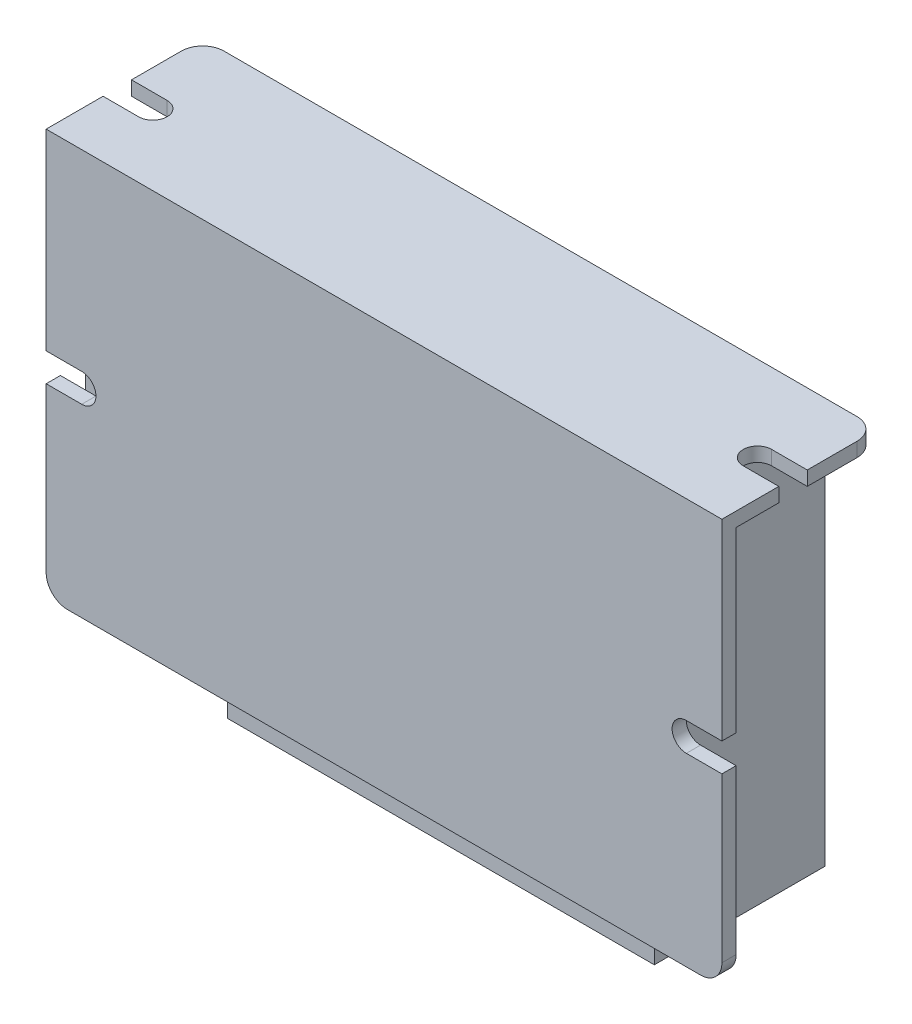
SolidWorks part; units mm, degrees
ref_plane "前视基准面" through (0, 0, 0) normal (0, 0, 1) x (1, 0, 0)
ref_plane "上视基准面" through (0, 0, 0) normal (0, 1, 0) x (1, 0, 0)
ref_plane "右视基准面" through (0, 0, 0) normal (1, 0, 0) x (0, 0, -1)
sketch "草图1" plane through (0, 0, 0) normal (0, 0, 1) x (1, 0, 0)
  line L1 (40, -27.5) -> (-40, -27.5)
  line L2 (40, -27.5) -> (40, 27.5)
  line L3 (40, 27.5) -> (-40, 27.5)
  line L4 (-40, -27.5) -> (-40, 27.5)
  line L5 (40, -27.5) -> (-40, 27.5) construction
  line L6 (40, 27.5) -> (-40, -27.5) construction
  point P0 (0, 0)
  dimension "D1" = 80
  dimension "D2" = 55
extrude "凸台-拉伸1" add sketch "草图1" along normal blind 20
sketch "草图2" plane through (0, 27.5, 0) normal (0, 1, 0) x (1, 0, 0)
  line L0 (-47.5, 0) -> (-47.5, -22)
  line L1 (-47.5, -22) -> (47.5, -22)
  line L2 (47.5, -22) -> (47.5, 0)
  line L3 (-47.5, 0) -> (-40, 0)
  line L4 (40, 0) -> (-40, 0)
  line L5 (-40, 0) -> (-40, -20)
  line L6 (-40, -20) -> (40, -20)
  line L7 (40, -20) -> (40, 0)
  line L8 (40, 0) -> (-40, 0)
  line L9 (40, -20) -> (-40, -20) construction
  line L12 (40, 0) -> (47.5, 0)
  line L13 (0, 0) -> (0, -13.9704) construction
  dimension "D2" = 95
  dimension "D3" = 2
  dimension "D1" = 0
extrude "凸台-拉伸2" add sketch "草图2" along normal blind 2 separate body
sketch "草图3" plane through (0, 27.5, 0) normal (0, -1, 0) x (1, 0, 0)
  line L0 (47.5, 22) -> (47.5, 0) construction
  line L1 (-47.5, 22) -> (47.5, 22)
  line L2 (-47.5, 22) -> (-47.5, 20)
  line L3 (-47.5, 20) -> (47.5, 20)
  line L4 (47.5, 22) -> (47.5, 20)
  line L5 (-40, 20) -> (40, 20) construction
extrude "凸台-拉伸3" add sketch "草图3" along normal up to surface (55 mm away) up to face at (0, -27.5, 10)
sketch "草图4" plane through (0, 0, 0) normal (1, 0, 0) x (0, 0, -1)
  line L0 (-1, -27.5) -> (-1, -28.5)
  line L1 (-20, -27.5) -> (0, -27.5) construction
  line L2 (-1, -28.5) -> (1, -28.5)
  line L3 (1, -28.5) -> (1, -37.5)
  line L4 (1, -37.5) -> (-14, -37.5)
  line L5 (-14, -37.5) -> (-14, -27.5)
  line L6 (-14, -27.5) -> (-1, -27.5)
  line L7 (0, -27.5) -> (0, 27.5) construction
  dimension "D1" = 1
  dimension "D2" = 1
  dimension "D3" = 1
  dimension "D4" = 15
  dimension "D5" = 10
extrude "凸台-拉伸4" add sketch "草图4" along normal mid plane 60
sketch "草图5" plane through (0, 27.5, 0) normal (0, -1, 0) x (1, 0, 0)
  line L0 (52.5, 12) -> (42.5, 12) construction
  line L1 (47.5, 20) -> (47.5, 0) construction
  line L2 (52.5, 10) -> (42.5, 10)
  line L3 (52.5, 14) -> (42.5, 14)
  line L4 (47.5, 0) -> (40, 0) construction
  arc A0 (52.5, 10) -> (52.5, 14) centre (52.5, 12) ccw
  arc A1 (42.5, 14) -> (42.5, 10) centre (42.5, 12) ccw
  point P4 (47.5, 12)
  dimension "D2" = 2
  dimension "D1" = 10
  dimension "D3" = 5
extrude "切除-拉伸1" cut sketch "草图5" against normal through all
sketch "草图6" plane through (0, 0, 20) normal (0, 0, -1) x (-1, 0, 0)
  line L0 (-52.5, 0.5) -> (-42.5, 0.5) construction
  line L1 (-47.5, -27.5) -> (-47.5, 27.5) construction
  line L2 (-52.5, 2.5) -> (-42.5, 2.5)
  line L3 (-52.5, -1.5) -> (-42.5, -1.5)
  line L4 (-47.5, -27.5) -> (-40, -27.5) construction
  arc A0 (-52.5, 2.5) -> (-52.5, -1.5) centre (-52.5, 0.5) ccw
  arc A1 (-42.5, -1.5) -> (-42.5, 2.5) centre (-42.5, 0.5) ccw
  point P4 (-47.5, 0.5)
  point P11 (-43.75, -27.5)
  dimension "D2" = 2
  dimension "D1" = 26
  dimension "D3" = 5
extrude "切除-拉伸2" cut sketch "草图6" against normal through all
mirror "镜向1" about plane through (0, 0, 0) normal (1, 0, 0) of "切除-拉伸2", "切除-拉伸1"
fillet "圆角1" radius 3 4 edges at (47.5, -27.5, 21) (-47.5, -27.5, 21) (47.5, 28.5, 0) (-47.5, 28.5, 0)
ref_plane "基准面1" through (0, 5.5, 0) normal (0, -1, 0) x (-1, 0, 0)
sketch "草图7" plane through (0, 5.5, 0) normal (0, -1, 0) x (-1, 0, 0)
  line L0 (40, -1) -> (41, -1)
  line L1 (40, -20) -> (40, 0) construction
  line L2 (41, -1) -> (41, 1)
  line L3 (41, 1) -> (50, 1)
  line L4 (50, 1) -> (50, -14)
  line L5 (50, -14) -> (40, -14)
  line L6 (40, -14) -> (40, -1)
  line L7 (40, 0) -> (-40, 0) construction
  dimension "D1" = 1
  dimension "D2" = 1
  dimension "D3" = 1
  dimension "D4" = 15
  dimension "D5" = 10
extrude "凸台-拉伸5" add sketch "草图7" along normal blind 15
